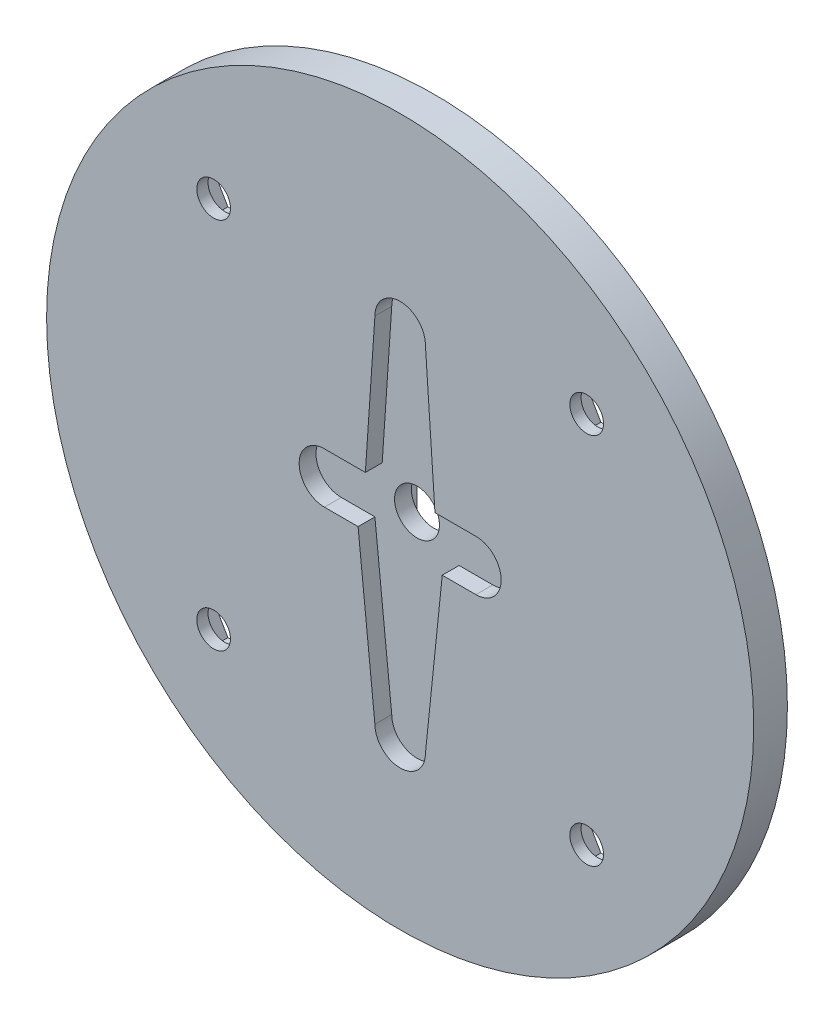
SolidWorks part; units mm, degrees
ref_plane "Alzado" through (0, 0, 0) normal (0, 0, 1) x (1, 0, 0)
ref_plane "Planta" through (0, 0, 0) normal (0, 1, 0) x (1, 0, 0)
ref_plane "Vista lateral" through (0, 0, 0) normal (1, 0, 0) x (0, 0, -1)
sketch "Croquis1" plane through (0, 0, 0) normal (0, 0, 1) x (1, 0, 0)
  line L1 (-21.1753, 30.481) -> (-65.7231, 30.481) construction
  line L3 (-65.7231, -14.0668) -> (-21.1753, -14.0668) construction
  line L4 (-21.1753, -14.0668) -> (-21.1753, 30.481) construction
  line L5 (-21.1753, 30.481) -> (-65.7231, -14.0668) construction
  line L6 (-65.7231, -14.0668) -> (-65.7231, 30.481) construction
  line L7 (-65.7231, 30.481) -> (-21.1753, -14.0668) construction
  circle A0 centre (-43.4492, 8.2071) radius 31.5
  circle A2 centre (-60.0662, 24.8241) radius 1.5
  circle A3 centre (-26.8322, 24.8241) radius 1.5
  circle A4 centre (-26.8322, -8.4099) radius 1.5
  circle A5 centre (-60.0662, -8.4099) radius 1.5
  circle A6 centre (-43.4492, 8.2071) radius 2
  dimension "D1" = 63
  dimension "D3" = 8
  dimension "D4" = 8
  dimension "D5" = 8
  dimension "D6" = 8
extrude "Saliente-Extruir1" add sketch "Croquis1" along normal blind 3
sketch "Croquis3" plane through (0, 0, 3) normal (0, 0, 1) x (1, 0, 0)
  line L0 (-43.4492, 8.2071) -> (-34.4492, 8.2071) construction
  line L1 (-43.4492, 8.2071) -> (-43.4492, -10.7929) construction
  line L2 (-43.4492, 8.2071) -> (-43.4492, 25.2071) construction
  line L3 (-43.4492, 8.2071) -> (-52.4492, 8.2071) construction
  line L4 (-43.4492, 8.2071) -> (-43.4492, 10.4571) construction
  line L5 (-52.4492, 8.2071) -> (-50.1992, 8.2071) construction
  line L6 (-43.4492, 10.4571) -> (-40.3492, 10.4571) construction
  line L7 (-43.4492, 10.4571) -> (-46.5492, 10.4571) construction
  line L10 (-43.4492, 25.2071) -> (-43.4492, 22.9571) construction
  line L11 (-43.4492, 22.9571) -> (-41.1992, 22.9571) construction
  line L13 (-43.4492, 22.9571) -> (-45.6992, 22.9571) construction
  line L15 (-41.1992, 22.9571) -> (-40.3492, 10.4571)
  line L16 (-45.6992, 22.9571) -> (-46.5492, 10.4571)
  line L17 (-43.4492, 8.2071) -> (-43.4492, 5.9571) construction
  line L18 (-43.4492, 5.9571) -> (-39.6992, 5.9571) construction
  line L19 (-43.4492, 5.9571) -> (-47.1992, 5.9571) construction
  line L22 (-43.4492, -10.7929) -> (-43.4492, -8.5429) construction
  line L23 (-43.4492, -8.5429) -> (-41.1992, -8.5429) construction
  line L25 (-43.4492, -8.5429) -> (-45.6992, -8.5429) construction
  line L26 (-47.1992, 5.9571) -> (-45.6992, -8.5429)
  line L27 (-39.6992, 5.9571) -> (-41.1992, -8.5429)
  line L28 (-46.5492, 10.4571) -> (-50.1992, 10.4571)
  line L29 (-47.1992, 5.9571) -> (-50.1992, 5.9571)
  line L30 (-34.4492, 8.2071) -> (-36.6992, 8.2071) construction
  line L31 (-40.3492, 10.4571) -> (-36.6992, 10.4571)
  line L32 (-39.6992, 5.9571) -> (-36.6992, 5.9571)
  arc A0 (-45.6992, 22.9571) -> (-41.1992, 22.9571) centre (-43.4492, 22.9571) cw
  arc A1 (-45.6992, -8.5429) -> (-41.1992, -8.5429) centre (-43.4492, -8.5429) ccw
  arc A2 (-50.1992, 5.9571) -> (-50.1992, 10.4571) centre (-50.1992, 8.2071) cw
  arc A3 (-36.6992, 10.4571) -> (-36.6992, 5.9571) centre (-36.6992, 8.2071) cw
  dimension "D1" = 17
  dimension "D2" = 19
  dimension "D3" = 9
  dimension "D4" = 9
  dimension "D5" = 2.25
  dimension "D6" = 2.25
extrude "Cortar-Extruir2" cut sketch "Croquis3" against normal blind 1.5
sketch "Croquis4" plane through (0, 0, 0) normal (0, 0, -1) x (-1, 0, 0)
  line L1 (35.9492, -4.2929) -> (50.9492, -4.2929)
  line L2 (35.9492, -4.2929) -> (35.9492, 20.7071)
  line L3 (35.9492, 20.7071) -> (50.9492, 20.7071)
  line L4 (50.9492, -4.2929) -> (50.9492, 20.7071)
  line L5 (35.9492, -4.2929) -> (50.9492, 20.7071) construction
  line L6 (35.9492, 20.7071) -> (50.9492, -4.2929) construction
  point P0 (43.4492, 8.2071)
  dimension "D1" = 15
  dimension "D2" = 25
extrude "Saliente-Extruir2" add sketch "Croquis4" along normal blind 3
sketch "Croquis5" plane through (0, -4.2929, 0) normal (0, -1, 0) x (1, 0, 0)
  line L0 (-35.9492, 0) -> (-32.9492, 0)
  line L1 (-32.9492, 0) -> (-35.9492, -3)
  line L2 (-35.9492, -3) -> (-35.9492, 0)
  line L3 (-50.9492, 0) -> (-53.9492, 0)
  line L4 (-53.9492, 0) -> (-50.9492, -3)
  line L5 (-50.9492, -3) -> (-50.9492, 0)
extrude "Saliente-Extruir3" add sketch "Croquis5" against normal up to vertex (25 mm away)
sketch "Croquis6" plane through (0, -4.2929, 0) normal (0, -1, 0) x (1, 0, 0)
  line L0 (-35.9492, 0) -> (-50.9492, 0)
  line L1 (-32.9492, 0) -> (-53.9492, 0) construction
  line L3 (-38.9492, -3) -> (-47.9492, -3)
  line L4 (-35.9492, -3) -> (-50.9492, -3) construction
  line L5 (-38.9492, -3) -> (-35.9492, 0)
  line L6 (-47.9492, -3) -> (-50.9492, 0)
  dimension "D1" = 3
  dimension "D2" = 3
  dimension "D3" = 3
  dimension "D4" = 3
extrude "Cortar-Extruir3" cut sketch "Croquis6" against normal blind 23
sketch "Croquis7" plane through (0, -4.2929, 0) normal (0, -1, 0) x (1, 0, 0)
  line L5 (-38.9492, -3) -> (-47.9492, -3) construction
  line L6 (-47.9492, -3) -> (-43.4492, -3) construction
  line L7 (-43.4492, -3) -> (-43.4492, 0.3572) construction
  line L12 (-39.1492, -3) -> (-36.6492, -0.5)
  line L17 (-39.1492, -3) -> (-38.7492, -3)
  line L18 (-38.7492, -3) -> (-36.2492, -0.5)
  line L20 (-36.6492, -0.5) -> (-36.2492, -0.5)
  line L21 (-50.2492, -0.5) -> (-50.6492, -0.5)
  line L22 (-48.1492, -3) -> (-50.6492, -0.5)
  line L23 (-47.7492, -3) -> (-48.1492, -3)
  line L24 (-47.7492, -3) -> (-50.2492, -0.5)
  line L25 (-32.9492, 0) -> (-35.9492, 0) construction
  dimension "D1" = 0.2
  dimension "D2" = 0.2
  dimension "D3" = 0.5
extrude "Saliente-Extruir4" add sketch "Croquis7" along normal blind 5
sketch "Croquis8" plane through (0, 0, 0) normal (0, 0, -1) x (-1, 0, 0)
  line L1 (30.2963, 24.8241) -> (28.5642, 27.8241)
  line L2 (28.5642, 27.8241) -> (25.1001, 27.8241)
  line L3 (25.1001, 27.8241) -> (23.3681, 24.8241)
  line L4 (23.3681, 24.8241) -> (25.1001, 21.8241)
  line L5 (25.1001, 21.8241) -> (28.5642, 21.8241)
  line L6 (28.5642, 21.8241) -> (30.2963, 24.8241)
  line L7 (63.5303, 24.8241) -> (61.7983, 27.8241)
  line L8 (61.7983, 27.8241) -> (58.3342, 27.8241)
  line L9 (58.3342, 27.8241) -> (56.6021, 24.8241)
  line L10 (56.6021, 24.8241) -> (58.3342, 21.8241)
  line L11 (58.3342, 21.8241) -> (61.7983, 21.8241)
  line L12 (61.7983, 21.8241) -> (63.5303, 24.8241)
  line L13 (30.2963, -8.4099) -> (28.5642, -5.4099)
  line L14 (28.5642, -5.4099) -> (25.1001, -5.4099)
  line L15 (25.1001, -5.4099) -> (23.3681, -8.4099)
  line L16 (23.3681, -8.4099) -> (25.1001, -11.4099)
  line L17 (25.1001, -11.4099) -> (28.5642, -11.4099)
  line L18 (28.5642, -11.4099) -> (30.2963, -8.4099)
  line L19 (63.5303, -8.4099) -> (61.7983, -5.4099)
  line L20 (61.7983, -5.4099) -> (58.3342, -5.4099)
  line L21 (58.3342, -5.4099) -> (56.6021, -8.4099)
  line L22 (56.6021, -8.4099) -> (58.3342, -11.4099)
  line L23 (58.3342, -11.4099) -> (61.7983, -11.4099)
  line L24 (61.7983, -11.4099) -> (63.5303, -8.4099)
  circle A0 centre (26.8322, 24.8241) radius 3 construction
  circle A1 centre (60.0662, 24.8241) radius 3 construction
  circle A2 centre (26.8322, -8.4099) radius 3 construction
  circle A3 centre (60.0662, -8.4099) radius 3 construction
  dimension "D1" = 6
  dimension "D2" = 6
extrude "Cortar-Extruir4" cut sketch "Croquis8" against normal blind 2
